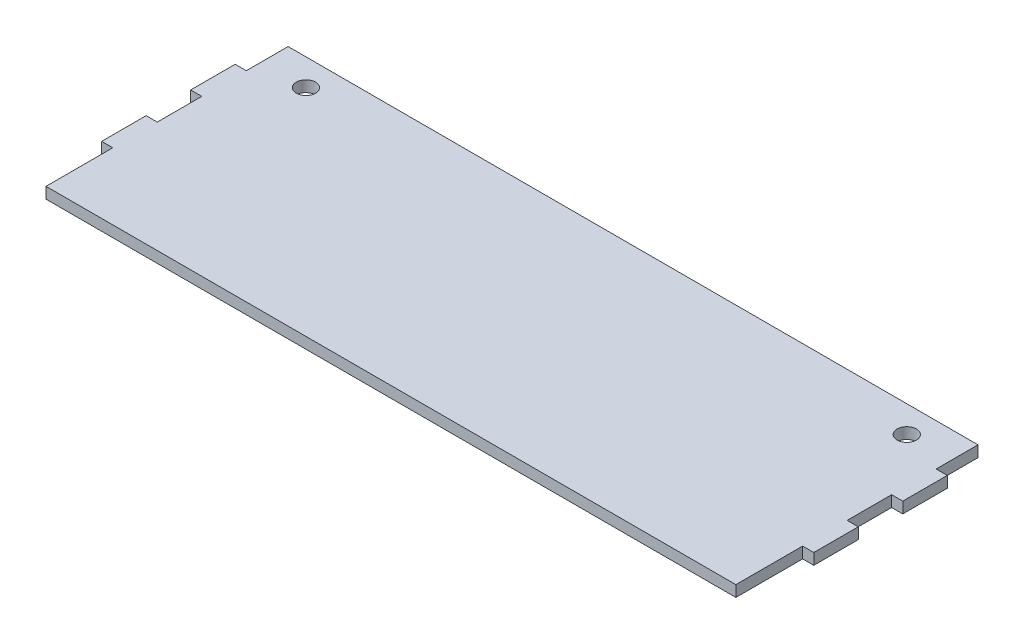
SolidWorks part; units mm, degrees
material "Acrylic (Medium-high impact)"
ref_plane "Front Plane" through (0, 0, 0) normal (0, 0, 1) x (1, 0, 0)
ref_plane "Top Plane" through (0, 0, 0) normal (0, 1, 0) x (1, 0, 0)
ref_plane "Right Plane" through (0, 0, 0) normal (1, 0, 0) x (0, 0, -1)
sketch "Sketch1" plane through (0, 0, 0) normal (0, 1, 0) x (1, 0, 0)
  line L0 (101.6, 69.088) -> (101.6, 0) construction
  line L37 (0, 0) -> (203.2, 0)
  line L38 (0, 0) -> (0, 69.088)
  line L39 (0, 69.088) -> (203.2, 69.088)
  line L40 (203.2, 0) -> (203.2, 69.088)
  line L41 (200.025, 57.15) -> (200.025, 69.088)
  line L42 (0, 0) -> (3.175, 0)
  line L43 (0, 0) -> (0, 19.05)
  line L44 (0, 19.05) -> (3.175, 19.05)
  line L45 (3.175, 0) -> (3.175, 19.05)
  line L46 (0, 31.75) -> (3.175, 31.75)
  line L47 (0, 31.75) -> (0, 44.45)
  line L48 (0, 44.45) -> (3.175, 44.45)
  line L49 (3.175, 31.75) -> (3.175, 44.45)
  line L50 (0, 57.15) -> (3.175, 57.15)
  line L51 (0, 57.15) -> (0, 69.088)
  line L52 (0, 69.088) -> (3.175, 69.088)
  line L53 (3.175, 57.15) -> (3.175, 69.088)
  line L54 (203.2, 69.088) -> (200.025, 69.088)
  line L55 (203.2, 57.15) -> (203.2, 69.088)
  line L56 (203.2, 57.15) -> (200.025, 57.15)
  line L57 (200.025, 31.75) -> (200.025, 44.45)
  line L58 (203.2, 44.45) -> (200.025, 44.45)
  line L59 (203.2, 31.75) -> (203.2, 44.45)
  line L60 (203.2, 31.75) -> (200.025, 31.75)
  line L61 (200.025, 0) -> (200.025, 19.05)
  line L62 (203.2, 19.05) -> (200.025, 19.05)
  line L63 (203.2, 0) -> (203.2, 19.05)
  line L64 (203.2, 0) -> (200.025, 0)
  line L65 (203.2, 0) -> (203.2, 69.088)
  dimension "D1" = 69.088
  dimension "D2" = 203.2
  dimension "D3" = 12.7
  dimension "D4" = 19.05
  dimension "D5" = 12.7
  dimension "D6" = 3.175
  dimension "D7" = 12.7
extrude "Boss-Extrude1" add sketch "Sketch1" along normal blind 3.175 contours L0 L39 L53 L50 L38 L48 L49 L46 L44 L45 L37 | L39 L0 L37 L61 L62 L40 L60 L57 L58 L56 L41
hole_wizard "M5 Clearance Hole1" positions "Sketch5" profile "Sketch6" hole size "M5" standard "ANSI Metric" end condition through all
sketch "Sketch5" plane through (0, 3.175, 0) normal (0, 1, 0) x (1, 0, 0)
  line L0 (200.025, 57.15) -> (200.025, 69.088) construction
  line L2 (3.175, 57.15) -> (3.175, 69.088) construction
  line L3 (3.175, 69.088) -> (200.025, 69.088) construction
  point P0 (15.875, 61.468)
  point P2 (187.325, 61.468)
  dimension "D1" = 12.7
  dimension "D2" = 12.7
  dimension "D3" = 7.62
  dimension "D4" = 7.62
sketch "Sketch6" plane through (15.875, 3.175, -61.468) normal (1, 0, 0) x (0, 0, 1)
  line L0 (0, 0) -> (0, 3.175)
  line L1 (0, 3.175) -> (2.75, 3.175)
  line L2 (2.75, 3.175) -> (2.75, 0)
  line L5 (2.75, 0) -> (0, 0)
  line L11 (0, -6.35) -> (0, 107.95) construction
  dimension "Thru Hole Dia." = 5.5
  dimension "Thru Hole Depth" = 3.175
